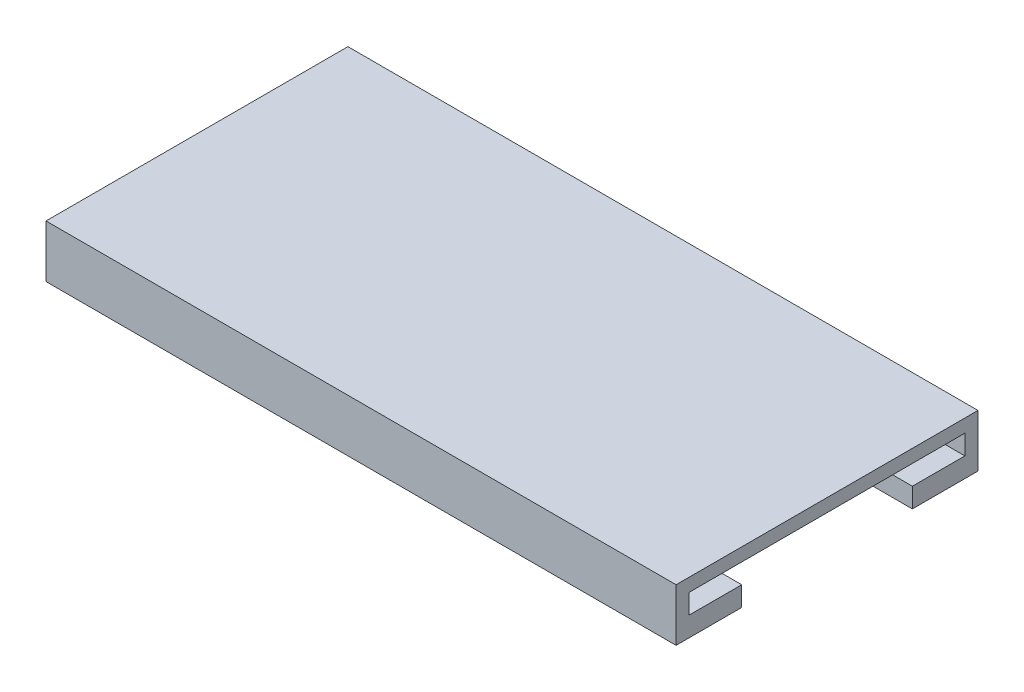
SolidWorks part; units mm, degrees
ref_plane "Front Plane" through (0, 0, 0) normal (0, 0, 1) x (1, 0, 0)
ref_plane "Top Plane" through (0, 0, 0) normal (0, 1, 0) x (1, 0, 0)
ref_plane "Right Plane" through (0, 0, 0) normal (1, 0, 0) x (0, 0, -1)
other "Bounding Box"
ref_plane "Default Plane" through (0, -3.175, 18.2563) normal (0, 0, -1) x (-1, 0, 0)
sketch "Sketch1" plane through (0, 0, 0) normal (1, 0, 0) x (0, 0, -1)
  line L0 (10.3187, -3.175) -> (18.2562, -3.175)
  line L1 (-18.2563, -3.175) -> (-10.3187, -3.175)
  line L2 (-18.2563, -3.175) -> (-18.2563, 3.175)
  line L3 (-18.2563, 3.175) -> (18.2562, 3.175)
  line L4 (18.2562, -3.175) -> (18.2562, 3.175)
  line L5 (-18.2563, -3.175) -> (10.0362, 1.7454) construction
  line L6 (-9.1281, 1.5875) -> (18.2562, -3.175) construction
  line L7 (16.6687, 1.5875) -> (-16.6687, 1.5875)
  line L8 (10.3187, -3.175) -> (10.3187, -0.7937)
  line L9 (10.3187, -0.7937) -> (16.6687, -0.7937)
  line L11 (-10.3187, -3.175) -> (-10.3187, -0.7937)
  line L14 (-10.3187, -0.7937) -> (-16.6687, -0.7938)
  line L16 (-16.6687, -0.7938) -> (-16.6687, 1.5875)
  line L17 (16.6687, -0.7937) -> (16.6687, 1.5875)
  point P0 (0, 0)
  dimension "D1" = 36.5125
  dimension "D2" = 6.35
  dimension "D3" = 2.3813
  dimension "D5" = 2.3813
  dimension "D8" = 6.35
extrude "Boss-Extrude1" add sketch "Sketch1" along normal blind 76.2
